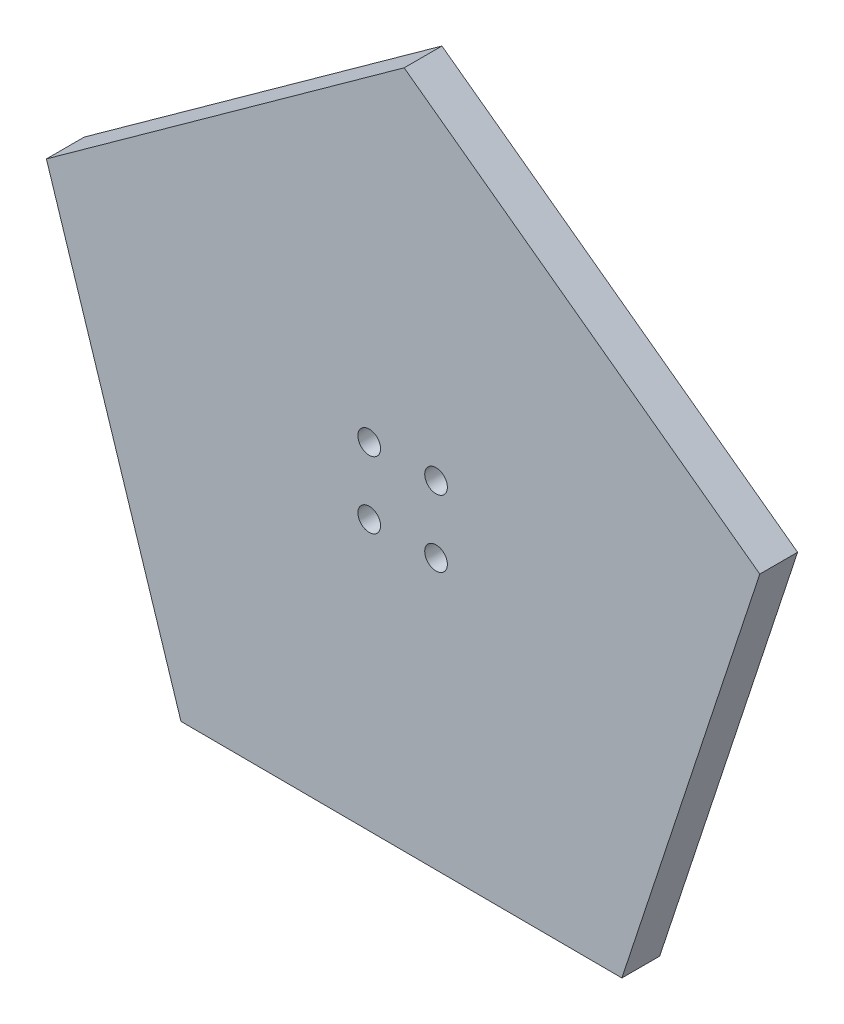
SolidWorks part; units mm, degrees
ref_plane "Front Plane" through (0, 0, 0) normal (0, 0, 1) x (1, 0, 0)
ref_plane "Top Plane" through (0, 0, 0) normal (0, 1, 0) x (1, 0, 0)
ref_plane "Right Plane" through (0, 0, 0) normal (1, 0, 0) x (0, 0, -1)
sketch "Sketch1" plane through (0, 0, 0) normal (0, 0, 1) x (1, 0, 0)
  line L1 (-17.5962, -24.0165) -> (17.4035, -24.1565)
  line L2 (17.4035, -24.1565) -> (28.3522, 9.0869)
  line L3 (28.3522, 9.0869) -> (0.1191, 29.7725)
  line L4 (0.1191, 29.7725) -> (-28.2786, 9.3135)
  line L5 (-28.2786, 9.3135) -> (-17.5962, -24.0165)
  circle A0 centre (0, 0) radius 24.0867 construction
  dimension "D1" = 35
extrude "Boss-Extrude1" add sketch "Sketch1" along normal blind 3 contours L4 L5 L1 L2 L3
sketch "Sketch2" plane through (0, 0, 0) normal (0, 0, -1) x (-1, 0, 0)
  line L0 (0, 0) -> (0, -3.75) construction
  line L1 (3.75, 0) -> (0, -3.75) construction
  line L2 (0, 0) -> (7.2512, -7.2512) construction
  circle A4 centre (2.6517, -2.6517) radius 0.9
  circle A5 centre (-2.6517, -2.6517) radius 0.9
  circle A6 centre (-2.6517, 2.6517) radius 0.9
  circle A7 centre (2.6517, 2.6517) radius 0.9
  point P13 (0, 0)
  point P17 (0, 0)
  dimension "D2" = 3.75
  dimension "D1" = 3.75
  dimension "D3" = 4
extrude "Cut-Extrude1" cut sketch "Sketch2" against normal blind 3
